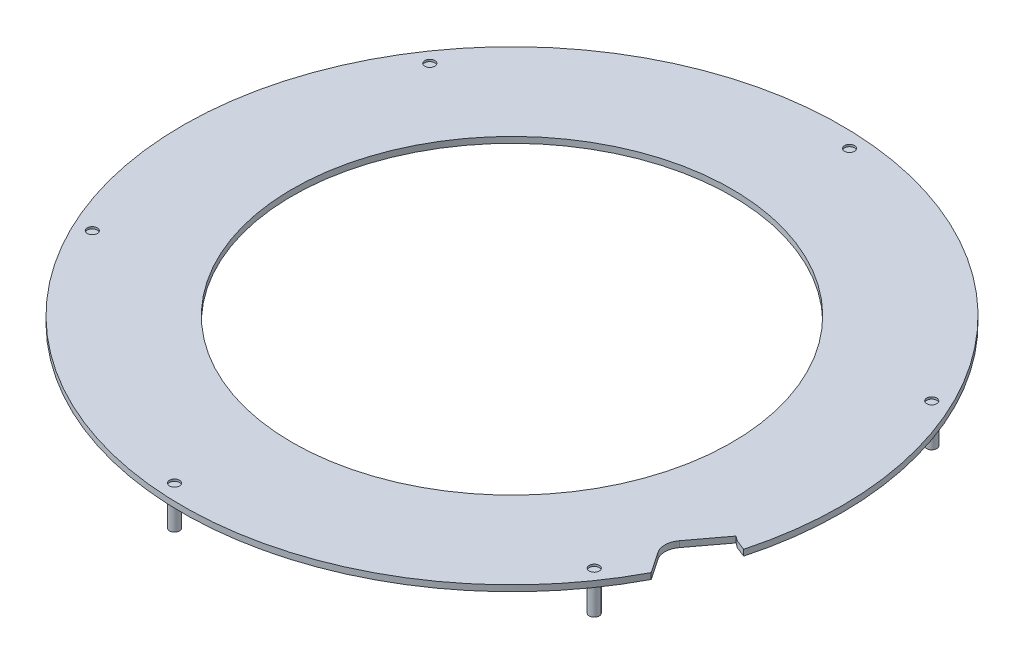
SolidWorks part; units mm, degrees
material "ASTM A36 Steel"
ref_plane "Front Plane" through (0, 0, 0) normal (0, 0, 1) x (1, 0, 0)
ref_plane "Top Plane" through (0, 0, 0) normal (0, 1, 0) x (1, 0, 0)
ref_plane "Right Plane" through (0, 0, 0) normal (1, 0, 0) x (0, 0, -1)
sketch "Sketch1" plane through (0, 0, 0) normal (0, 1, 0) x (1, 0, 0)
  circle A0 centre (0, 0) radius 165
  circle A1 centre (0, 0) radius 110
  dimension "D1" = 220
  dimension "D2" = 330
extrude "Boss-Extrude1" add sketch "Sketch1" along normal blind 3
sketch "Sketch4" plane through (0, 0, 0) normal (0, -1, 0) x (1, 0, 0)
  circle A0 centre (-11.9437, 157.0465) radius 2.5
  circle A1 centre (0, 0) radius 157.5 construction
  dimension "D1" = 315
  dimension "D2" = 5
extrude "Boss-Extrude2" add sketch "Sketch4" along normal blind 16.5
pattern_circular "CirPattern1" count 6 over 360 about axis through (0, 0, 0) along (0, 1, 0) of "Boss-Extrude2"
sketch "Sketch5" plane through (0, 0, 0) normal (0, -1, 0) x (-1, 0, 0)
  line L16 (-139.4182, -55.6681) -> (-151.5937, -39.4145)
  line L17 (-151.5937, -39.4145) -> (-153.89, -41.1346)
  line L18 (-153.89, -41.1346) -> (-160.1564, -43.657)
  line L19 (-146.8249, -77.4496) -> (-139.1622, -66.0999)
  arc A8 (-160.1564, -43.657) -> (-146.8249, -77.4496) centre (0, 0) ccw
  arc A9 (-139.1622, -66.0999) -> (-139.4182, -55.6681) centre (-146.6213, -61.0639) ccw
extrude "Cut-Extrude1" cut sketch "Sketch5" against normal blind 10
sketch "Sketch6" plane through (0, 3, 0) normal (0, 1, 0) x (1, 0, 0)
  circle A0 centre (11.9437, 157.0465) radius 2.5
extrude "Cut-Extrude2" cut sketch "Sketch6" against normal blind 1
pattern_circular "CirPattern5" count 6 every 60 about axis through (0, 0, 0) along (0, 1, 0) of "Cut-Extrude2"
